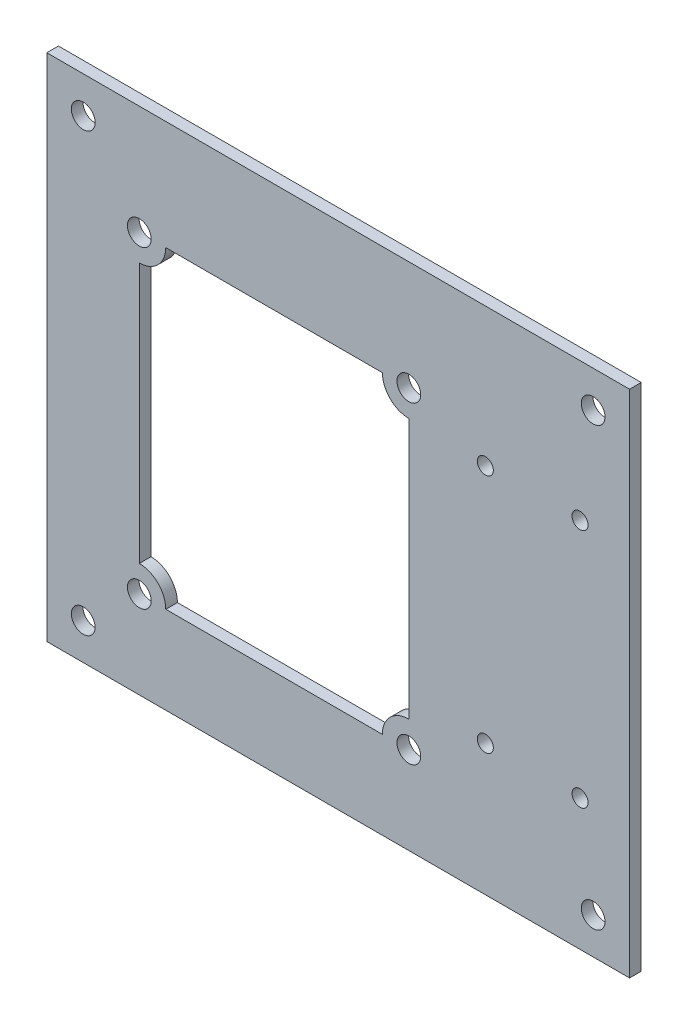
SolidWorks part; units mm, degrees
ref_plane "Front Plane" through (0, 0, 0) normal (0, 0, 1) x (1, 0, 0)
ref_plane "Top Plane" through (0, 0, 0) normal (0, 1, 0) x (1, 0, 0)
ref_plane "Right Plane" through (0, 0, 0) normal (1, 0, 0) x (0, 0, -1)
sketch "Sketch1" plane through (0, 0, 0) normal (0, 0, 1) x (1, 0, 0)
  line L0 (7.7, -10) -> (7.7, -53) construction
  line L1 (0, 0) -> (70, 0) construction
  line L2 (0, 0) -> (0, -60) construction
  line L3 (0, -60) -> (70, -60) construction
  line L4 (70, 0) -> (70, -60) construction
  line L5 (-5, 5) -> (75, 5)
  line L6 (-5, 5) -> (-5, -65)
  line L7 (-5, -65) -> (75, -65)
  line L8 (75, 5) -> (75, -65)
  line L9 (7.7, -53) -> (44.7, -53) construction
  line L10 (44.7, -53) -> (44.7, -10) construction
  line L11 (7.7, -10) -> (44.7, -10) construction
  line L12 (11.332, -10) -> (41.068, -10)
  line L13 (44.7, -13.6319) -> (44.7, -49.368)
  line L14 (7.7, -13.6319) -> (7.7, -49.368)
  line L15 (11.332, -53) -> (41.068, -53)
  line L17 (55.2, -14) -> (68.2, -14) construction
  line L18 (55.2, -14) -> (55.2, -47) construction
  line L19 (55.2, -47) -> (68.2, -47) construction
  line L20 (68.2, -14) -> (68.2, -47) construction
  line L21 (49.7, -11) -> (73.7, -11) construction
  line L22 (49.7, -11) -> (49.7, -50) construction
  line L23 (49.7, -50) -> (73.7, -50) construction
  line L24 (73.7, -11) -> (73.7, -50) construction
  circle A0 centre (0, 0) radius 1.632
  circle A1 centre (70, 0) radius 1.6319
  circle A2 centre (70, -60) radius 1.6319
  circle A3 centre (0, -60) radius 1.6319
  circle A4 centre (7.7, -10) radius 1.632
  circle A5 centre (44.7, -10) radius 1.6319
  circle A6 centre (44.7, -53) radius 1.6319
  circle A7 centre (7.7, -53) radius 1.6319
  circle A8 centre (7.7, -10) radius 3.6319
  circle A9 centre (44.7, -10) radius 3.632
  circle A10 centre (44.7, -53) radius 3.6319
  circle A11 centre (7.7, -53) radius 3.6319
  circle A12 centre (55.2, -14) radius 1.1
  circle A13 centre (68.2, -14) radius 1.1
  circle A14 centre (68.2, -47) radius 1.1
  circle A15 centre (55.2, -47) radius 1.1
  point P33 (26.2, -31.5)
  point P34 (26.2, -10)
  point P35 (44.7, -31.5)
  point P48 (49.5, -11.9991)
  point P49 (68.5033, -17.2276)
  dimension "D3" = 3.2639
  dimension "D8" = 3.2639
  dimension "D18" = 2.2
  dimension "D1" = 70
  dimension "D2" = 60
  dimension "D4" = 5
  dimension "D5" = 5
  dimension "D6" = 5
  dimension "D7" = 5
  dimension "D9" = 37
  dimension "D10" = 43
  dimension "D11" = 2
  dimension "D12" = 12.7
  dimension "D13" = 15
  dimension "D14" = 33
  dimension "D15" = 39
  dimension "D16" = 24
  dimension "D17" = 13
  dimension "D19" = 3
  dimension "D20" = 5.5
  dimension "D21" = 5
  dimension "D22" = 15
extrude "Boss-Extrude1" add sketch "Sketch1" along normal blind 1.6 contours L8 L5 L6 L7 A11 L14 A8 L12 A9 L13 A10 L15 A3 A2 A1 A0 | A8 A4 | A9 A5 | A10 A6 | A11 A7
equation "\"D6@Sketch1\"=\"D4@Sketch1\""
equation "\"D7@Sketch1\"=\"D4@Sketch1\""
equation "\"D5@Sketch1\"=\"D4@Sketch1\""
equation "\"D19@Sketch1\"=(\"D15@Sketch1\"-\"D14@Sketch1\")/2"
equation "\"D20@Sketch1\"=(\"D16@Sketch1\"-\"D17@Sketch1\")/2"
